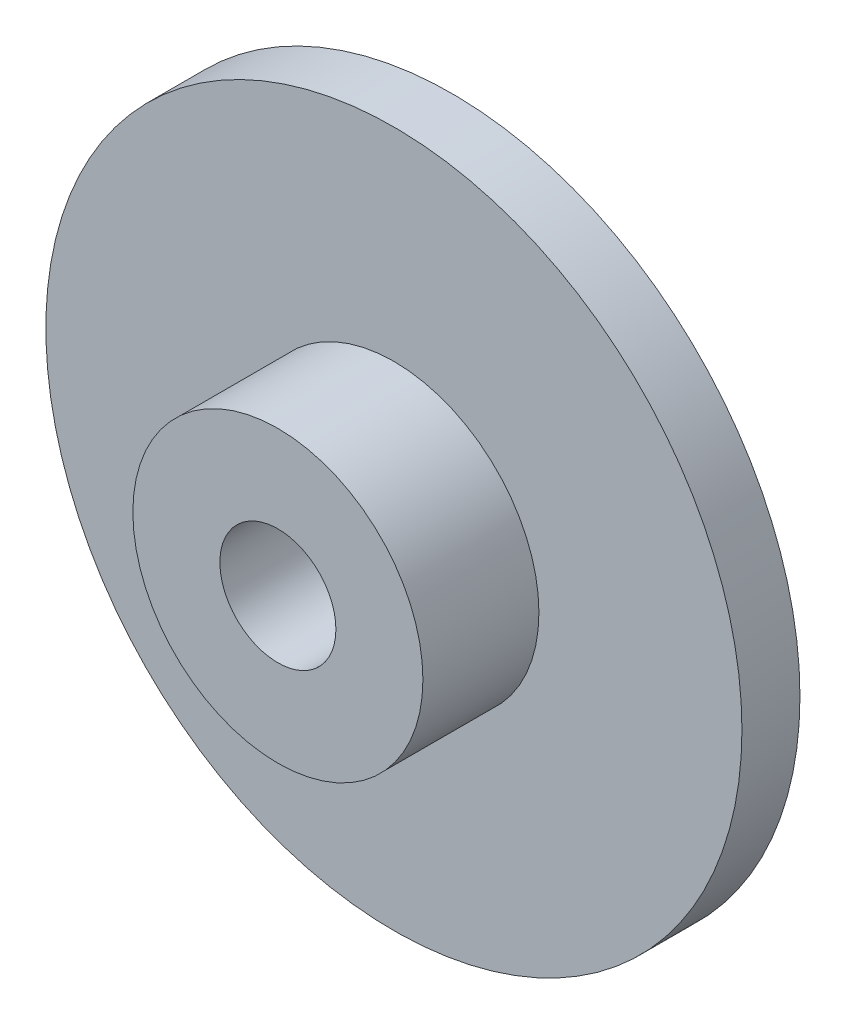
SolidWorks part; units mm, degrees
ref_plane "Front Plane" through (0, 0, 0) normal (0, 0, 1) x (1, 0, 0)
ref_plane "Top Plane" through (0, 0, 0) normal (0, 1, 0) x (1, 0, 0)
ref_plane "Right Plane" through (0, 0, 0) normal (1, 0, 0) x (0, 0, -1)
sketch "Sketch1" plane through (0, 0, 0) normal (0, 0, 1) x (1, 0, 0)
  circle A0 centre (0, 0) radius 19.05
  dimension "D1" = 38.1
extrude "Boss-Extrude1" add sketch "Sketch1" along normal blind 3.175
sketch "Sketch2" plane through (0, 0, 3.175) normal (0, 0, 1) x (1, 0, 0)
  circle A0 centre (0, 0) radius 7.9375
  dimension "D1" = 15.875
extrude "Boss-Extrude2" add sketch "Sketch2" along normal blind 6.35
sketch "Sketch3" plane through (0, 0, 9.525) normal (0, 0, 1) x (1, 0, 0)
  circle A0 centre (0, 0) radius 3.175
  dimension "D1" = 6.35
extrude "Cut-Extrude1" cut sketch "Sketch3" against normal through all
